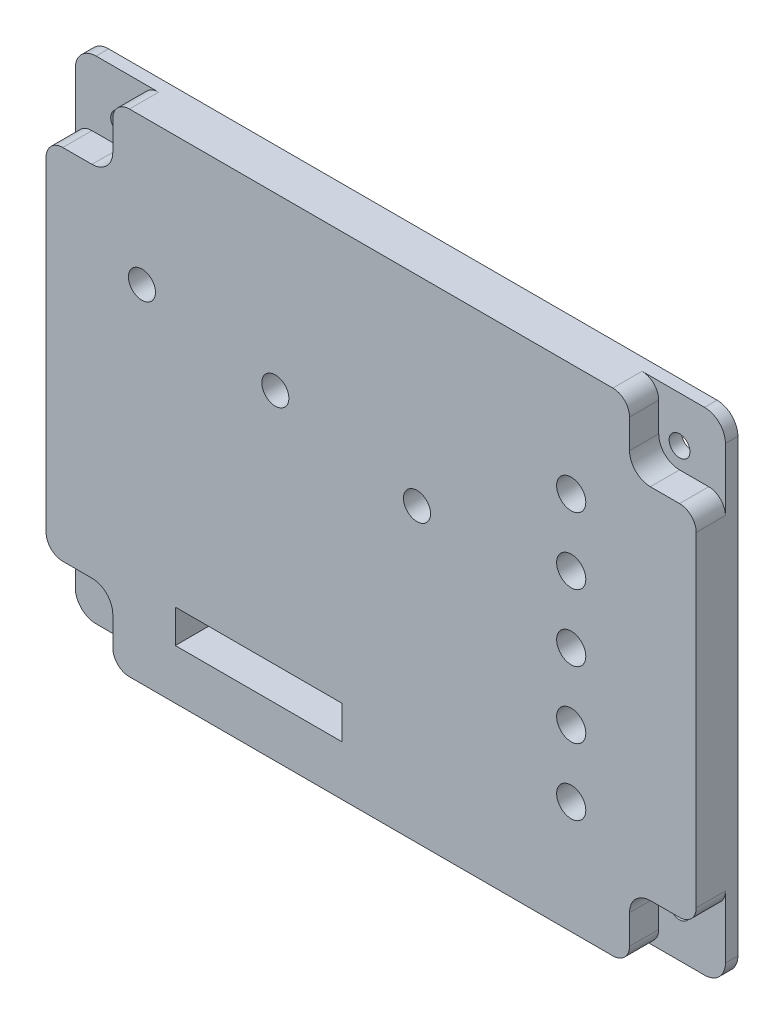
SolidWorks part; units mm, degrees
ref_plane "Front Plane" through (0, 0, 0) normal (0, 0, 1) x (1, 0, 0)
ref_plane "Top Plane" through (0, 0, 0) normal (0, 1, 0) x (1, 0, 0)
ref_plane "Right Plane" through (0, 0, 0) normal (1, 0, 0) x (0, 0, -1)
sketch "Sketch1" plane through (0, 0, 0) normal (0, 0, 1) x (1, 0, 0)
  line L1 (-67.6147, 37.6971) -> (78.3853, 37.6971)
  line L2 (-72.6147, 32.6971) -> (-72.6147, -75.3029)
  line L3 (-67.6147, -80.3029) -> (78.3853, -80.3029)
  line L4 (83.3853, 32.6971) -> (83.3853, -75.3029)
  line L5 (-41.6147, -60.3029) -> (-1.6147, -60.3029)
  line L6 (-41.6147, -60.3029) -> (-41.6147, -68.3029)
  line L7 (-41.6147, -68.3029) -> (-1.6147, -68.3029)
  line L8 (-1.6147, -60.3029) -> (-1.6147, -68.3029)
  circle A0 centre (-49.6147, 2.6971) radius 3.25
  circle A1 centre (-17.6147, -3.3029) radius 3.25
  circle A2 centre (16.3853, -10.3029) radius 3.25
  circle A3 centre (53.3853, 10.6971) radius 3.5
  circle A4 centre (53.3853, -5.3029) radius 3.5
  circle A5 centre (53.3853, -21.3029) radius 3.5
  circle A6 centre (53.3853, -37.3029) radius 3.5
  circle A7 centre (53.3853, -53.3029) radius 3.5
  arc A8 (-72.6147, -75.3029) -> (-67.6147, -80.3029) centre (-67.6147, -75.3029) ccw
  arc A9 (78.3853, -80.3029) -> (83.3853, -75.3029) centre (78.3853, -75.3029) ccw
  arc A10 (83.3853, 32.6971) -> (78.3853, 37.6971) centre (78.3853, 32.6971) ccw
  arc A11 (-72.6147, 32.6971) -> (-67.6147, 37.6971) centre (-67.6147, 32.6971) cw
  point P26 (-72.6147, -80.3029)
  point P31 (83.3853, 37.6971)
  point P34 (-72.6147, 37.6971)
  dimension "D5" = 6.5
  dimension "D8" = 6.5
  dimension "D11" = 6.5
  dimension "D16" = 7
  dimension "D22" = 7
  dimension "D23" = 7
  dimension "D24" = 7
  dimension "D26" = 7
  dimension "D27" = 5
  dimension "D1" = 156
  dimension "D2" = 118
  dimension "D3" = 23
  dimension "D4" = 35
  dimension "D6" = 55
  dimension "D7" = 41
  dimension "D9" = 89
  dimension "D10" = 48
  dimension "D12" = 40
  dimension "D13" = 8
  dimension "D14" = 12
  dimension "D15" = 31
  dimension "D17" = 27
  dimension "D18" = 30
  dimension "D19" = 16
  dimension "D20" = 16
  dimension "D21" = 16
  dimension "D25" = 16
extrude "Boss-Extrude1" add sketch "Sketch1" along normal blind 10
sketch "Sketch2" plane through (0, 0, 10) normal (0, 0, 1) x (1, 0, 0)
  line L1 (-72.6147, 37.6971) -> (-56.6147, 37.6971)
  line L2 (-72.6147, 37.6971) -> (-72.6147, 21.6971)
  line L3 (-72.6147, 21.6971) -> (-61.6147, 21.6971)
  line L4 (-56.6147, 37.6971) -> (-56.6147, 26.6971)
  line L5 (83.3853, 37.6971) -> (67.3853, 37.6971)
  line L6 (83.3853, 37.6971) -> (83.3853, 21.6971)
  line L7 (83.3853, 21.6971) -> (72.3853, 21.6971)
  line L8 (67.3853, 37.6971) -> (67.3853, 26.6971)
  line L9 (83.3853, -80.3029) -> (67.3853, -80.3029)
  line L10 (83.3853, -80.3029) -> (83.3853, -64.3029)
  line L11 (83.3853, -64.3029) -> (72.3853, -64.3029)
  line L12 (67.3853, -80.3029) -> (67.3853, -69.3029)
  line L13 (-72.6147, -80.3029) -> (-56.6147, -80.3029)
  line L14 (-72.6147, -80.3029) -> (-72.6147, -64.3029)
  line L15 (-72.6147, -64.3029) -> (-61.6147, -64.3029)
  line L16 (-56.6147, -80.3029) -> (-56.6147, -69.3029)
  arc A0 (-56.6147, 26.6971) -> (-61.6147, 21.6971) centre (-61.6147, 26.6971) cw
  arc A1 (67.3853, 26.6971) -> (72.3853, 21.6971) centre (72.3853, 26.6971) ccw
  arc A2 (72.3853, -64.3029) -> (67.3853, -69.3029) centre (72.3853, -69.3029) ccw
  arc A3 (-56.6147, -69.3029) -> (-61.6147, -64.3029) centre (-61.6147, -69.3029) ccw
  point P22 (-56.6147, 21.6971)
  point P25 (67.3853, 21.6971)
  point P28 (67.3853, -64.3029)
  point P31 (-56.6147, -64.3029)
  dimension "D9" = 5
  dimension "D1" = 16
  dimension "D2" = 16
  dimension "D3" = 16
  dimension "D4" = 16
  dimension "D5" = 16
  dimension "D6" = 16
  dimension "D7" = 16
  dimension "D8" = 16
extrude "Cut-Extrude1" cut sketch "Sketch2" against normal blind 7
sketch "Sketch3" plane through (0, 0, 3) normal (0, 0, 1) x (1, 0, 0)
  line L0 (-56.6147, 26.6971) -> (-56.6147, 37.6971) construction
  line L1 (-72.6147, 21.6971) -> (-61.6147, 21.6971) construction
  line L2 (67.3853, 37.6971) -> (67.3853, 26.6971) construction
  line L3 (72.3853, 21.6971) -> (83.3853, 21.6971) construction
  line L4 (83.3853, -64.3029) -> (72.3853, -64.3029) construction
  line L5 (67.3853, -69.3029) -> (67.3853, -80.3029) construction
  line L6 (-61.6147, -64.3029) -> (-72.6147, -64.3029) construction
  line L7 (-56.6147, -80.3029) -> (-56.6147, -69.3029) construction
  circle A0 centre (-61.6147, 26.6971) radius 2.5
  circle A1 centre (72.3853, 26.6971) radius 2.5
  circle A2 centre (72.3853, -69.3029) radius 2.5
  circle A3 centre (-61.6147, -69.3029) radius 2.5
  dimension "D3" = 5
  dimension "D6" = 5
  dimension "D7" = 5
  dimension "D10" = 5
  dimension "D12" = 5
  dimension "D1" = 5
  dimension "D2" = 5
  dimension "D4" = 5
  dimension "D5" = 5
  dimension "D8" = 5
  dimension "D9" = 5
  dimension "D11" = 5
extrude "Cut-Extrude2" cut sketch "Sketch3" against normal blind 10
fillet "Fillet1" radius 4 8 edges at (67.3853, -80.3029, 6.5) (83.3853, -64.3029, 6.5) (83.3853, 21.6971, 6.5) (67.3853, 37.6971, 6.5) (-56.6147, 37.6971, 6.5) (-72.6147, 21.6971, 6.5) (-56.6147, -80.3029, 6.5) (-72.6147, -64.3029, 6.5)
